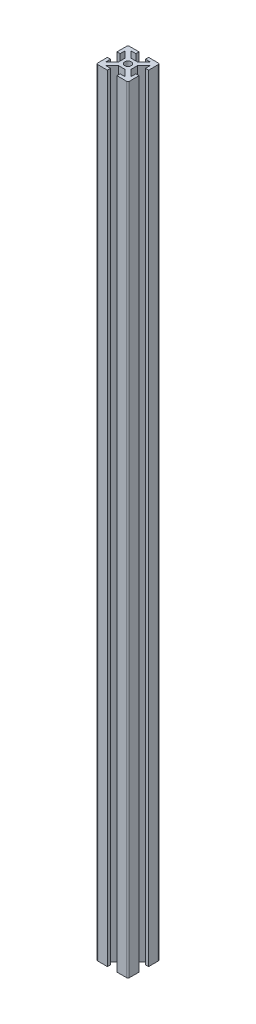
SolidWorks part; units mm, degrees
ref_plane "前视基准面" through (0, 0, 0) normal (0, 0, 1) x (1, 0, 0)
ref_plane "上视基准面" through (0, 0, 0) normal (0, 1, 0) x (1, 0, 0)
ref_plane "右视基准面" through (0, 0, 0) normal (1, 0, 0) x (0, 0, -1)
sketch "草图1" plane through (0, 0, 0) normal (0, 1, 0) x (1, 0, 0)
  line L0 (10, 10) -> (3, 10)
  line L1 (-10, -10) -> (10, -10) construction
  line L2 (-10, -10) -> (-10, 10) construction
  line L3 (-10, 10) -> (10, 10) construction
  line L4 (10, -10) -> (10, 10) construction
  line L5 (-10, -10) -> (10, 10) construction
  line L6 (-10, 10) -> (10, -10) construction
  line L7 (-4, -4) -> (4, -4) construction
  line L8 (-4, -4) -> (-4, 4) construction
  line L9 (-4, 4) -> (4, 4) construction
  line L10 (4, -4) -> (4, 4) construction
  line L11 (-4, -4) -> (4, 4) construction
  line L12 (-4, 4) -> (4, -4) construction
  line L13 (3, 10) -> (3, 8)
  line L14 (3, 8) -> (6, 8)
  line L15 (6, 8) -> (2, 4)
  line L16 (10, 3) -> (8, 3)
  line L17 (8, 6) -> (4, 2)
  line L18 (8, 3) -> (8, 6)
  line L19 (10, 10) -> (10, 3)
  line L20 (8, -6) -> (4, -2)
  line L21 (8, -3) -> (8, -6)
  line L22 (10, -3) -> (8, -3)
  line L23 (10, -10) -> (10, -3)
  line L24 (6, -8) -> (2, -4)
  line L25 (3, -8) -> (6, -8)
  line L26 (3, -10) -> (3, -8)
  line L27 (10, -10) -> (3, -10)
  line L28 (-6, -8) -> (-2, -4)
  line L29 (-3, -8) -> (-6, -8)
  line L30 (-3, -10) -> (-3, -8)
  line L31 (-10, -10) -> (-3, -10)
  line L32 (-8, -6) -> (-4, -2)
  line L33 (-8, -3) -> (-8, -6)
  line L34 (-10, -3) -> (-8, -3)
  line L35 (-10, -10) -> (-10, -3)
  line L36 (-8, 6) -> (-4, 2)
  line L37 (-8, 3) -> (-8, 6)
  line L38 (-10, 3) -> (-8, 3)
  line L39 (-10, 10) -> (-10, 3)
  line L40 (-6, 8) -> (-2, 4)
  line L41 (-3, 8) -> (-6, 8)
  line L42 (-3, 10) -> (-3, 8)
  line L43 (-10, 10) -> (-3, 10)
  line L44 (-4, 2) -> (-4, -2)
  line L45 (-2, -4) -> (2, -4)
  line L46 (4, -2) -> (4, 2)
  line L47 (2, 4) -> (-2, 4)
  circle A0 centre (0, 0) radius 2.1
  point P0 (0, 0)
  point P50 (0, 0)
  dimension "D2" = 4.2
  dimension "D1" = 20
  dimension "D3" = 8
  dimension "D4" = 3
  dimension "D5" = 6
  dimension "D6" = 2
  dimension "D7" = 4
extrude "凸台-拉伸1" add sketch "草图1" along normal blind 490
fillet "圆角1" radius 1 4 edges at (-10, 245, 10) (10, 245, 10) (-10, 245, -10) (10, 245, -10)
